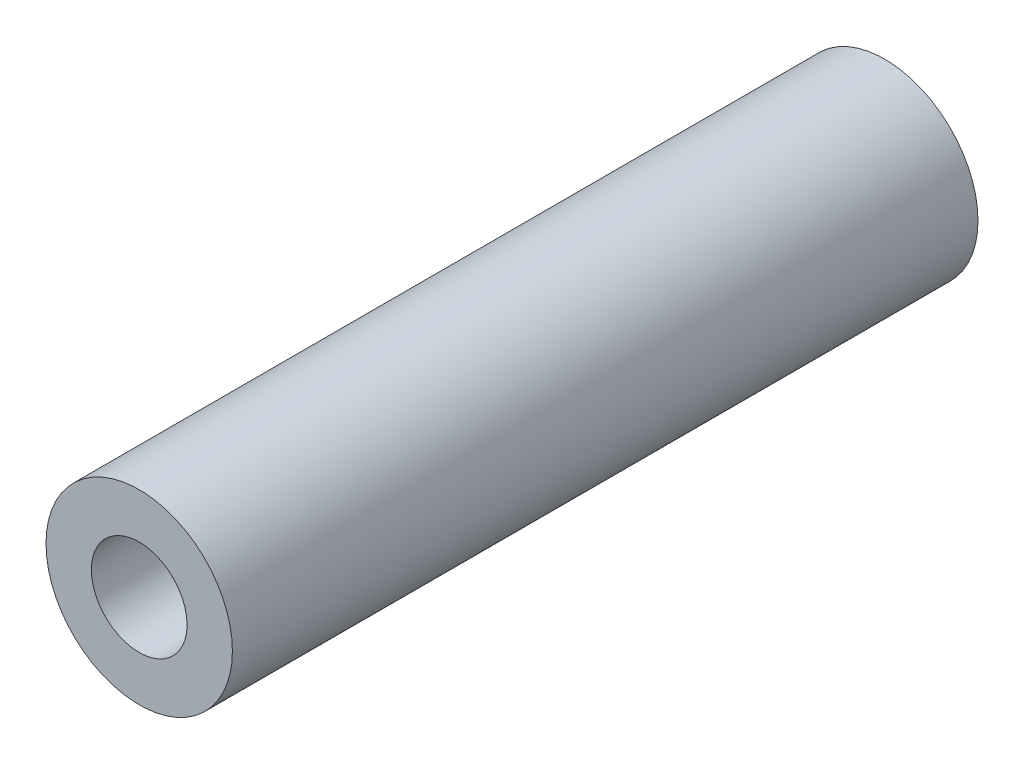
SolidWorks part; units mm, degrees
ref_plane "Front Plane" through (0, 0, 0) normal (0, 0, 1) x (1, 0, 0)
ref_plane "Top Plane" through (0, 0, 0) normal (0, 1, 0) x (1, 0, 0)
ref_plane "Right Plane" through (0, 0, 0) normal (1, 0, 0) x (0, 0, -1)
sketch "Sketch1" plane through (0, 0, 0) normal (0, 0, 1) x (1, 0, 0)
  circle A0 centre (0, 0) radius 9.525
  circle A1 centre (0, 0) radius 4.8895
  dimension "OD" = 19.05
  dimension "ID" = 9.779
extrude "Extrude1" add sketch "Sketch1" along normal mid plane 76.2
sketch "Sketch2" plane through (0, 0, 0) normal (1, 0, 0) x (0, 0, -1)
  line L0 (-38.1, -4.8895) -> (38.1, -4.8895) construction
  line L3 (38.1, 4.8895) -> (-38.1, 4.8895) construction
  line L5 (-38.1, -4.8895) -> (38.1, -4.8895)
  line L6 (38.1, 4.8895) -> (-38.1, 4.8895)
sketch "Sketch4" plane through (0, 0, 38.1) normal (0, 0, 1) x (1, 0, 0)
  line L0 (0, 0) -> (-3.4574, 3.4574)
  line L1 (0, -10.4775) -> (0, 10.4775) construction
  circle A0 centre (0, 0) radius 4.8895 construction
  dimension "D1" = 45
